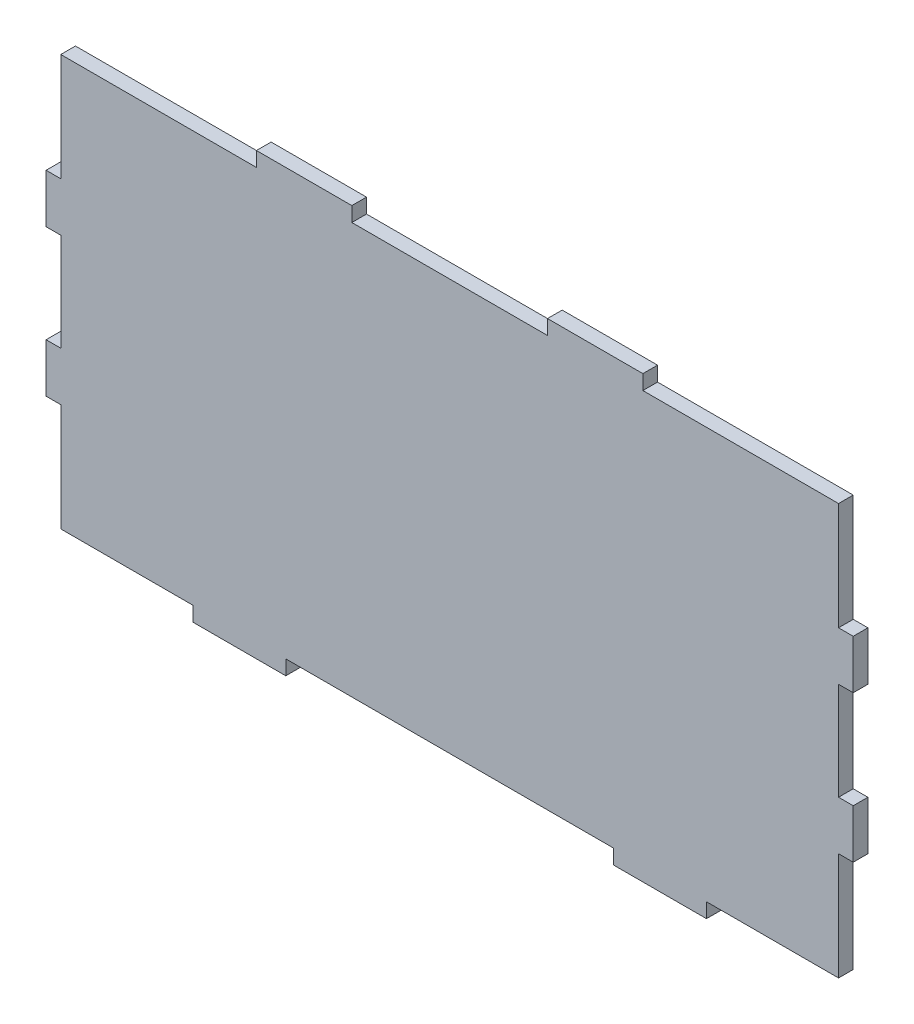
SolidWorks part; units mm, degrees
ref_plane "Plan de face" through (0, 0, 0) normal (0, 0, 1) x (1, 0, 0)
ref_plane "Plan de dessus" through (0, 0, 0) normal (0, 1, 0) x (1, 0, 0)
ref_plane "Plan de droite" through (0, 0, 0) normal (1, 0, 0) x (0, 0, -1)
sketch "Esquisse1" plane through (0, 0, 0) normal (0, 0, 1) x (1, 0, 0)
  line L1 (0, 0) -> (-330, 0)
  line L2 (0, 0) -> (0, 180)
  line L3 (0, 180) -> (-330, 180)
  line L4 (-330, 0) -> (-330, 180)
  dimension "D1" = 180
  dimension "D2" = 330
extrude "Boss.-Extru.1" add sketch "Esquisse1" along normal blind 6
sketch "Esquisse2" plane through (0, 0, 6) normal (0, 0, 1) x (1, 0, 0)
  line L0 (-330, 180) -> (-330, 0) construction
  line L2 (-330, 180) -> (-330, 130)
  line L3 (-330, 130) -> (-324, 130)
  line L4 (-324, 174) -> (-324, 130)
  line L6 (-330, 0) -> (-330, 50)
  line L7 (-330, 50) -> (-324, 50)
  line L8 (-324, 6) -> (-324, 50)
  line L9 (-330, 70) -> (-324, 70)
  line L10 (-330, 70) -> (-330, 110)
  line L11 (-330, 110) -> (-324, 110)
  line L12 (-324, 70) -> (-324, 110)
  line L13 (0, 0) -> (0, 180) construction
  line L15 (0, 180) -> (0, 130)
  line L16 (0, 130) -> (-6, 130)
  line L17 (-6, 174) -> (-6, 130)
  line L19 (0, 0) -> (0, 50)
  line L20 (0, 50) -> (-6, 50)
  line L21 (-6, 6) -> (-6, 50)
  line L22 (0, 70) -> (-6, 70)
  line L23 (0, 70) -> (0, 110)
  line L24 (0, 110) -> (-6, 110)
  line L25 (-6, 70) -> (-6, 110)
  line L26 (0, 180) -> (-330, 180) construction
  line L27 (-330, 180) -> (-244, 180)
  line L29 (-324, 174) -> (-244, 174)
  line L30 (-244, 180) -> (-244, 174)
  line L31 (-205, 180) -> (-125, 180)
  line L32 (-205, 180) -> (-205, 174)
  line L33 (-205, 174) -> (-125, 174)
  line L34 (-125, 180) -> (-125, 174)
  line L35 (-330, 0) -> (0, 0) construction
  line L36 (0, 180) -> (-86, 180)
  line L38 (-6, 174) -> (-86, 174)
  line L39 (-86, 180) -> (-86, 174)
  line L40 (-330, 0) -> (-270, 0)
  line L42 (-324, 6) -> (-270, 6)
  line L43 (-270, 0) -> (-270, 6)
  line L44 (-232, 0) -> (-98, 0)
  line L45 (-232, 0) -> (-232, 6)
  line L46 (-232, 6) -> (-98, 6)
  line L47 (-98, 0) -> (-98, 6)
  line L49 (0, 0) -> (-60, 0)
  line L51 (-6, 6) -> (-60, 6)
  line L52 (-60, 0) -> (-60, 6)
  dimension "D1" = 6
  dimension "D2" = 6
  dimension "D3" = 6
  dimension "D4" = 40
  dimension "D5" = 20
  dimension "D6" = 20
  dimension "D7" = 86
  dimension "D8" = 40
  dimension "D9" = 50
  dimension "D10" = 60
  dimension "D11" = 6
  dimension "D12" = 6
  dimension "D13" = 6
  dimension "D14" = 20
  dimension "D15" = 6
  dimension "D16" = 50
  dimension "D17" = 6
  dimension "D18" = 80
  dimension "D19" = 39
  dimension "D20" = 6
  dimension "D21" = 39
  dimension "D22" = 50
  dimension "D23" = 54
  dimension "D24" = 6
  dimension "D25" = 6
  dimension "D26" = 38
  dimension "D27" = 38
  dimension "D28" = 6
extrude "Enlèv. mat.-Extru.1" cut sketch "Esquisse2" against normal through all
